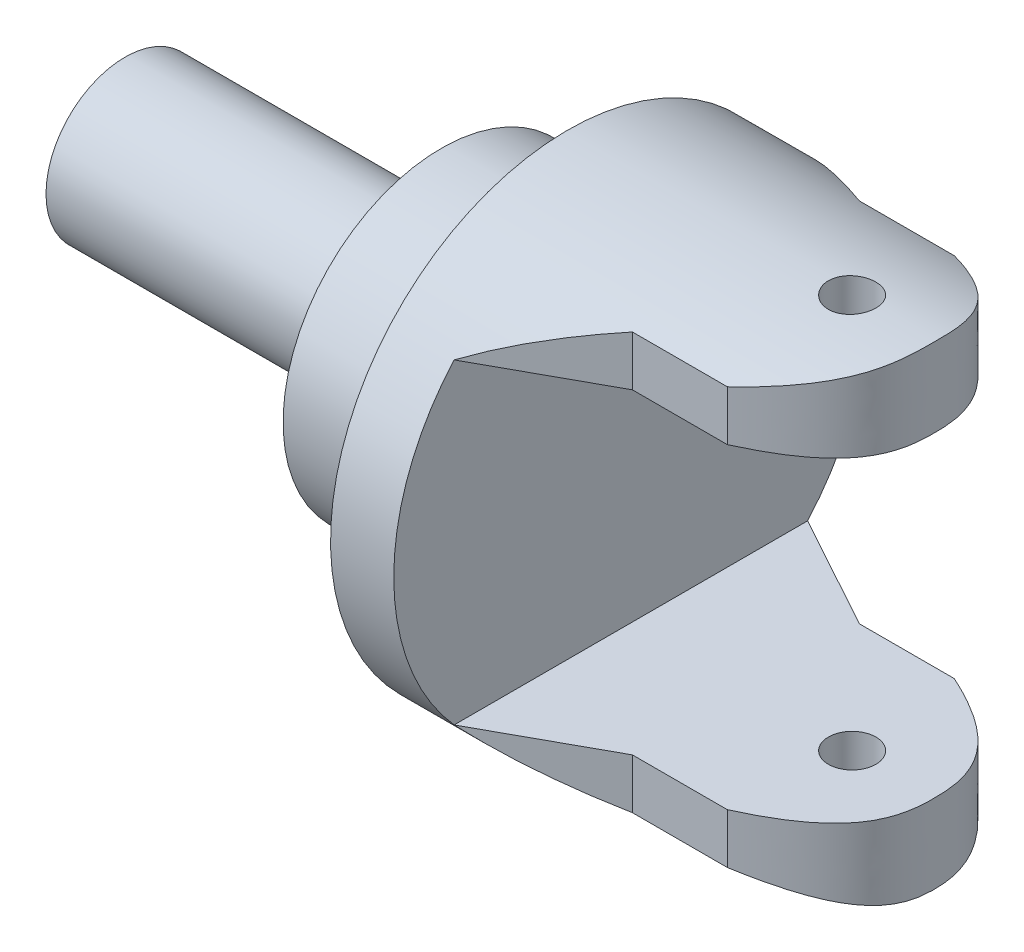
SolidWorks part; units mm, degrees
ref_plane "Front Plane" through (0, 0, 0) normal (0, 0, 1) x (1, 0, 0)
ref_plane "Top Plane" through (0, 0, 0) normal (0, 1, 0) x (1, 0, 0)
ref_plane "Right Plane" through (0, 0, 0) normal (1, 0, 0) x (0, 0, -1)
sketch "Sketch1" plane through (0, 0, 0) normal (1, 0, 0) x (0, 0, -1)
  circle A0 centre (0, 0) radius 5
  dimension "D1" = 10
extrude "Boss-Extrude1" add sketch "Sketch1" along normal blind 4
sketch "Sketch2" plane through (4, 0, 0) normal (1, 0, 0) x (0, 0, -1)
  circle A0 centre (0, 0) radius 7.5
  dimension "D1" = 15
extrude "Boss-Extrude2" add sketch "Sketch2" along normal blind 2
sketch "Sketch3" plane through (6, 0, 0) normal (1, 0, 0) x (0, 0, -1)
  line L1 (-5.5902, -5) -> (5.5902, -5)
  line L2 (-5.5902, -5) -> (-5.5902, 5)
  line L3 (-5.5902, 5) -> (5.5902, 5)
  line L4 (5.5902, -5) -> (5.5902, 5)
  line L5 (-5.5902, -5) -> (5.5902, 5) construction
  line L6 (-5.5902, 5) -> (5.5902, -5) construction
  arc A0 (-4.899, 5) -> (-4.899, -5) centre (0, 0) ccw
  circle A1 centre (0, 0) radius 7.5 construction
  arc A2 (4.899, -5) -> (4.899, 5) centre (0, 0) ccw
  point P0 (0, 0)
  circle M2 centre (0, 0) radius 7.5
  dimension "D1" = 10
extrude "Boss-Extrude3" add sketch "Sketch3" along normal blind 10 contours L3 M2 | L1 M2
sketch "Sketch4" plane through (0, 5, 0) normal (0, -1, 0) x (1, 0, 0)
  line L0 (16, 0) -> (5.8747, 0) construction
  line L1 (16, 5.5902) -> (16, -5.5902) construction
  line L7 (6, 5.5902) -> (16, 5.5902)
  line L8 (16, 5.5902) -> (16, -5.5902)
  line L9 (16, -5.5902) -> (6, -5.5902)
  line L10 (12.6404, 3.5902) -> (9.6404, 3.5902)
  line L11 (9.6404, 3.5902) -> (6, 5.5902)
  line L12 (12.6404, -3.5902) -> (9.6404, -3.5902)
  line L13 (9.6404, -3.5902) -> (6, -5.5902)
  spline S0 degree 3 poles (12.6404, -3.5902) (15.2801, -2.3934) (15.9199, 0) (15.2801, 2.3934) (12.6404, 3.5902) knots 0.178885 0.178885 0.178885 0.178885 0.5 0.821115 0.821115 0.821115 0.821115
  dimension "D1" = 9.6
  dimension "D2" = 3
  dimension "D3" = 2
  dimension "D4" = 3
  dimension "D5" = 2
extrude "Cut-Extrude1" cut sketch "Sketch4" against normal through all both and the other way through all
sketch "Sketch5" plane through (0, 5, 0) normal (0, -1, 0) x (1, 0, 0)
  line L0 (6, 0) -> (17.8474, 0) construction
  line L1 (6, 5.5902) -> (6, -5.5902) construction
  circle A0 centre (13, 0) radius 0.75
  dimension "D2" = 1.5
  dimension "D1" = 7
extrude "Cut-Extrude2" cut sketch "Sketch5" against normal through all both and the other way through all
sketch "Sketch6" plane through (0, 0, 0) normal (-1, 0, 0) x (0, 0, 1)
  circle A0 centre (0, 0) radius 2.5
  dimension "D1" = 5
extrude "Boss-Extrude4" add sketch "Sketch6" along normal blind 10
